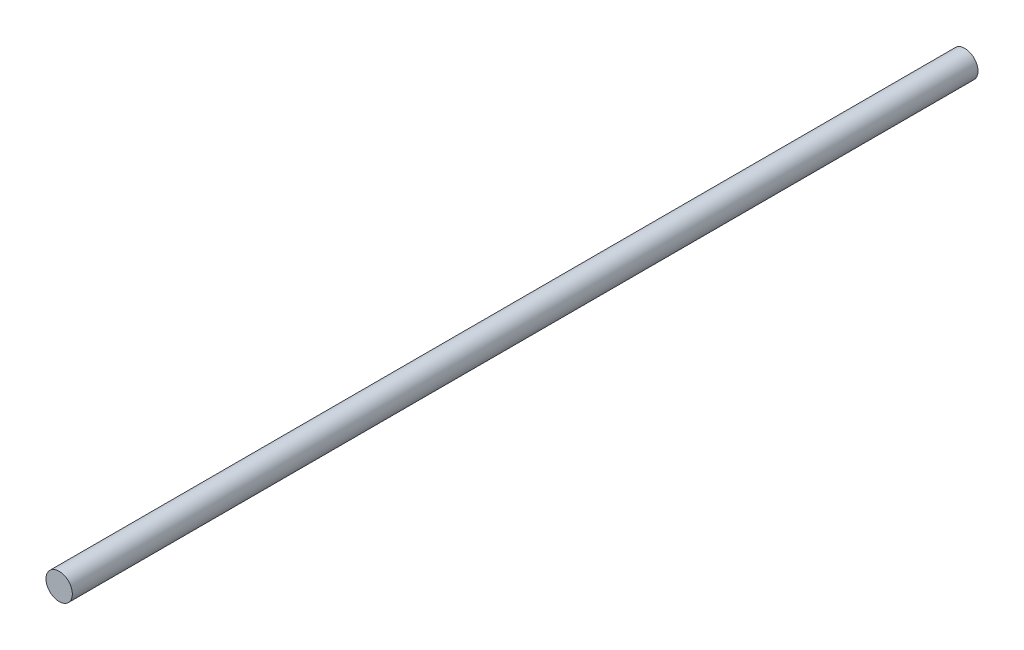
SolidWorks part; units mm, degrees
ref_plane "Alzado" through (0, 0, 0) normal (0, 0, 1) x (1, 0, 0)
ref_plane "Planta" through (0, 0, 0) normal (0, 1, 0) x (1, 0, 0)
ref_plane "Vista lateral" through (0, 0, 0) normal (1, 0, 0) x (0, 0, -1)
sketch "Croquis1" plane through (0, 0, 0) normal (0, 0, 1) x (1, 0, 0)
  circle A0 centre (0, 0) radius 8
  dimension "D1" = 16
extrude "Saliente-Extruir1" add sketch "Croquis1" along normal blind 550
